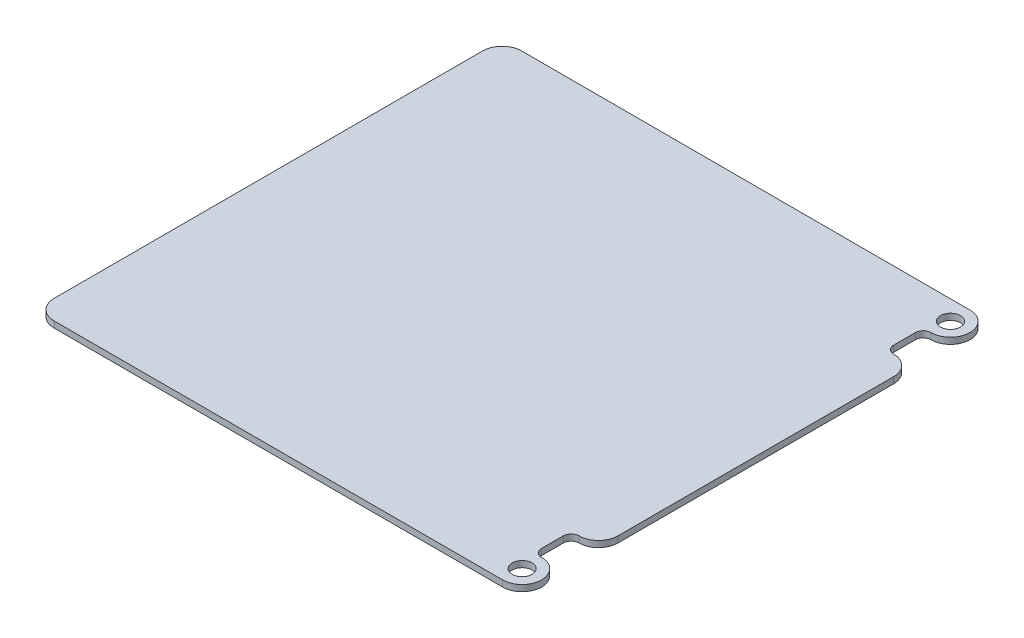
SolidWorks part; units mm, degrees
ref_plane "前视基准面" through (0, 0, 0) normal (0, 0, 1) x (1, 0, 0)
ref_plane "上视基准面" through (0, 0, 0) normal (0, 1, 0) x (1, 0, 0)
ref_plane "右视基准面" through (0, 0, 0) normal (1, 0, 0) x (0, 0, -1)
sketch "草图1" plane through (0, 0, 0) normal (0, 1, 0) x (1, 0, 0)
  line L0 (-738.301, -638.4923) -> (-623.301, -638.4923)
  line L1 (-625.301, -626.4923) -> (-625.301, -620.9223)
  line L5 (-743.3657, -523.5578) -> (-743.3657, -633.5578)
  line L8 (-625.301, -530.6234) -> (-625.301, -536.1934)
  line L9 (-738.3657, -518.5578) -> (-623.301, -518.6234)
  line L10 (-618.301, -543.1934) -> (-618.301, -613.9223)
  arc A1 (-738.301, -638.4923) -> (-743.3657, -633.5578) centre (-738.3661, -633.4927) cw
  arc A2 (-623.301, -638.4923) -> (-618.301, -633.4923) centre (-623.301, -633.4923) ccw
  arc A3 (-618.301, -633.4923) -> (-623.301, -628.4923) centre (-623.301, -633.4923) ccw
  arc A4 (-623.301, -628.4923) -> (-625.301, -626.4923) centre (-623.301, -626.4923) cw
  arc A5 (-625.301, -620.9223) -> (-623.301, -618.9223) centre (-623.301, -620.9223) cw
  arc A6 (-623.301, -618.9223) -> (-618.301, -613.9223) centre (-623.301, -613.9223) ccw
  arc A12 (-738.3657, -518.5578) -> (-743.3657, -523.5578) centre (-738.3657, -523.5578) ccw
  arc A16 (-623.301, -538.1934) -> (-618.301, -543.1934) centre (-623.301, -543.1934) cw
  arc A17 (-625.301, -536.1934) -> (-623.301, -538.1934) centre (-623.301, -536.1934) ccw
  arc A18 (-623.301, -528.6234) -> (-625.301, -530.6234) centre (-623.301, -530.6234) ccw
  arc A19 (-618.301, -523.6234) -> (-623.301, -528.6234) centre (-623.301, -523.6234) cw
  arc A20 (-623.301, -518.6234) -> (-618.301, -523.6234) centre (-623.301, -523.6234) cw
  circle A21 centre (-623.301, -633.4923) radius 2.55
  circle A22 centre (-623.301, -523.6234) radius 2.55
  dimension "D1" = 5.1
  dimension "D2" = 5.1
extrude "凸台-拉伸1" add sketch "草图1" along normal blind 1.6
